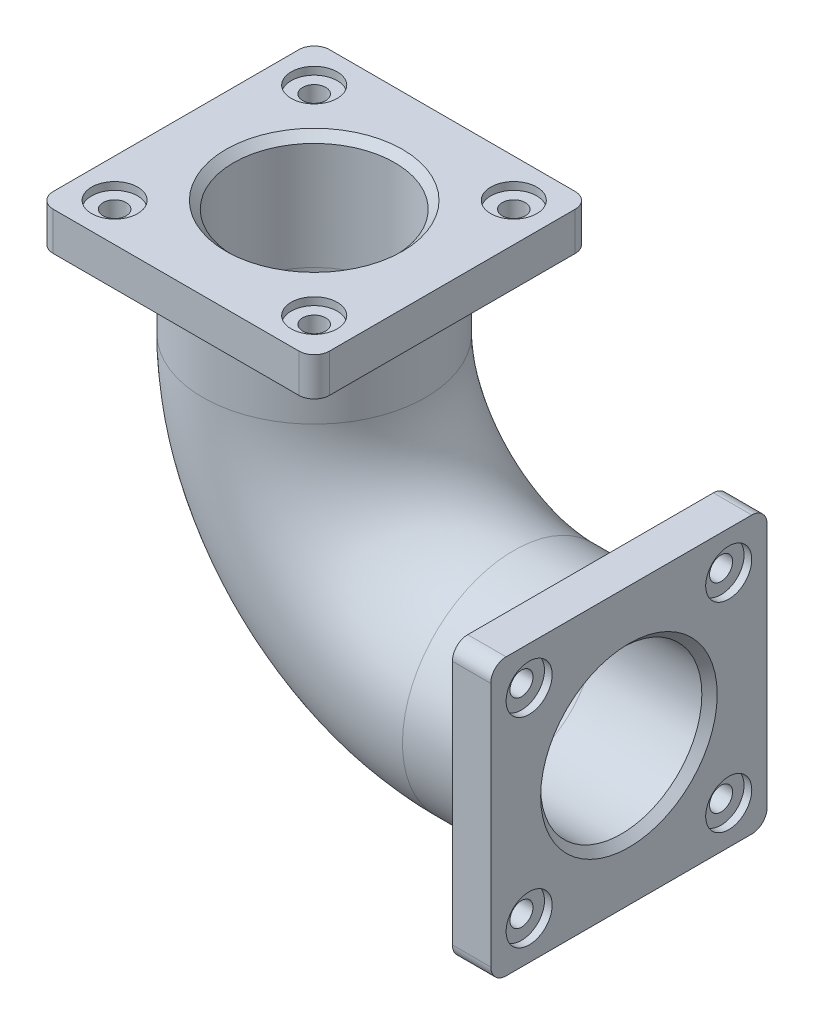
SolidWorks part; units mm, degrees
ref_plane "Front Plane" through (0, 0, 0) normal (0, 0, 1) x (1, 0, 0)
ref_plane "Top Plane" through (0, 0, 0) normal (0, 1, 0) x (1, 0, 0)
ref_plane "Right Plane" through (0, 0, 0) normal (1, 0, 0) x (0, 0, -1)
sketch "Sketch1" plane through (0, 0, 0) normal (0, 0, 1) x (1, 0, 0)
  line L0 (0, 0) -> (-150, 0)
  line L1 (-410, 260) -> (-410, 410)
  arc A0 (-150, 0) -> (-410, 260) centre (-150, 260) cw
  dimension "D1" = 150
  dimension "D3" = 260
  dimension "D2" = 150
ref_plane "Plane1" through (-410, 410, 0) normal (0, 1, 0) x (1, 0, 0)
sketch "Sketch2" plane through (-410, 410, 0) normal (0, 1, 0) x (1, 0, 0)
  circle A0 centre (0, 0) radius 145
  circle A1 centre (0, 0) radius 105
  dimension "D1" = 290
  dimension "D2" = 210
sweep "Sweep1" add profiles "Sketch2" path "Sketch1"
sketch "Sketch6" plane through (0, 0, 0) normal (1, 0, 0) x (0, 0, -1)
  line L0 (-180, 0) -> (180, 0) construction
  line L1 (-160, -180) -> (160, -180)
  line L2 (-180, -160) -> (-180, 160)
  line L3 (-160, 180) -> (160, 180)
  line L4 (180, -160) -> (180, 160)
  line L5 (-180, -180) -> (180, 180) construction
  line L6 (-180, 180) -> (180, -180) construction
  line L7 (0, 180) -> (0, -180) construction
  arc A0 (180, 160) -> (160, 180) centre (160, 160) ccw
  arc A1 (180, -160) -> (160, -180) centre (160, -160) cw
  arc A2 (-160, -180) -> (-180, -160) centre (-160, -160) cw
  arc A3 (-180, 160) -> (-160, 180) centre (-160, 160) cw
  circle A4 centre (130, 130) radius 15
  circle A7 centre (130, -130) radius 15
  circle A8 centre (-130, -130) radius 15
  circle A10 centre (-130, 130) radius 15
  circle A14 centre (0, 0) radius 145 construction
  circle A15 centre (0, 0) radius 145
  point P0 (0, 0)
  dimension "D3" = 20
  dimension "D5" = 30
  dimension "D1" = 360
  dimension "D2" = 360
  dimension "D6" = 130
extrude "Boss-Extrude1" add sketch "Sketch6" against normal blind 50
chamfer "Chamfer1" distance 10 angle 45 1 edges at (0, -105, 0)
fillet "Fillet1" radius 10 1 edges at (-50, 0, -145)
sketch "Sketch7" plane through (0, 410, 0) normal (0, 1, 0) x (1, 0, 0)
  line L0 (-590, 0) -> (-230, 0) construction
  line L1 (-570, -180) -> (-250, -180)
  line L2 (-590, -160) -> (-590, 160)
  line L3 (-570, 180) -> (-250, 180)
  line L4 (-230, -160) -> (-230, 160)
  line L5 (-590, -180) -> (-230, 180) construction
  line L6 (-590, 180) -> (-230, -180) construction
  line L7 (-410, 180) -> (-410, -180) construction
  arc A0 (-570, -180) -> (-590, -160) centre (-570, -160) cw
  arc A1 (-230, -160) -> (-250, -180) centre (-250, -160) cw
  arc A2 (-230, 160) -> (-250, 180) centre (-250, 160) ccw
  arc A3 (-590, 160) -> (-570, 180) centre (-570, 160) cw
  circle A5 centre (-540, 130) radius 15
  circle A6 centre (-540, -130) radius 15
  circle A8 centre (-280, -130) radius 15
  circle A10 centre (-280, 130) radius 15
  circle A12 centre (-410, 0) radius 145 construction
  circle A13 centre (-410, 0) radius 145
  point P0 (-410, 0)
  dimension "D3" = 20
  dimension "D5" = 30
  dimension "D1" = 360
  dimension "D2" = 360
  dimension "D6" = 130
extrude "Boss-Extrude2" add sketch "Sketch7" against normal blind 50
chamfer "Chamfer2" distance 10 angle 45 1 edges at (-515, 410, 0)
fillet "Fillet2" radius 10 1 edges at (-555, 360, 0)
sketch "Sketch9" plane through (0, 410, 0) normal (0, 1, 0) x (1, 0, 0)
  circle A0 centre (-540, 130) radius 30
  circle A1 centre (-280, 130) radius 30
  circle A2 centre (-540, -130) radius 30
  circle A3 centre (-280, -130) radius 30
  dimension "D1" = 60
extrude "Cut-Extrude1" cut sketch "Sketch9" against normal blind 10
sketch "Sketch10" plane through (0, 0, 0) normal (1, 0, 0) x (0, 0, -1)
  circle A0 centre (-130, 130) radius 30
  circle A1 centre (130, 130) radius 30
  circle A2 centre (-130, -130) radius 30
  circle A3 centre (130, -130) radius 30
  dimension "D1" = 60
extrude "Cut-Extrude2" cut sketch "Sketch10" against normal blind 10
